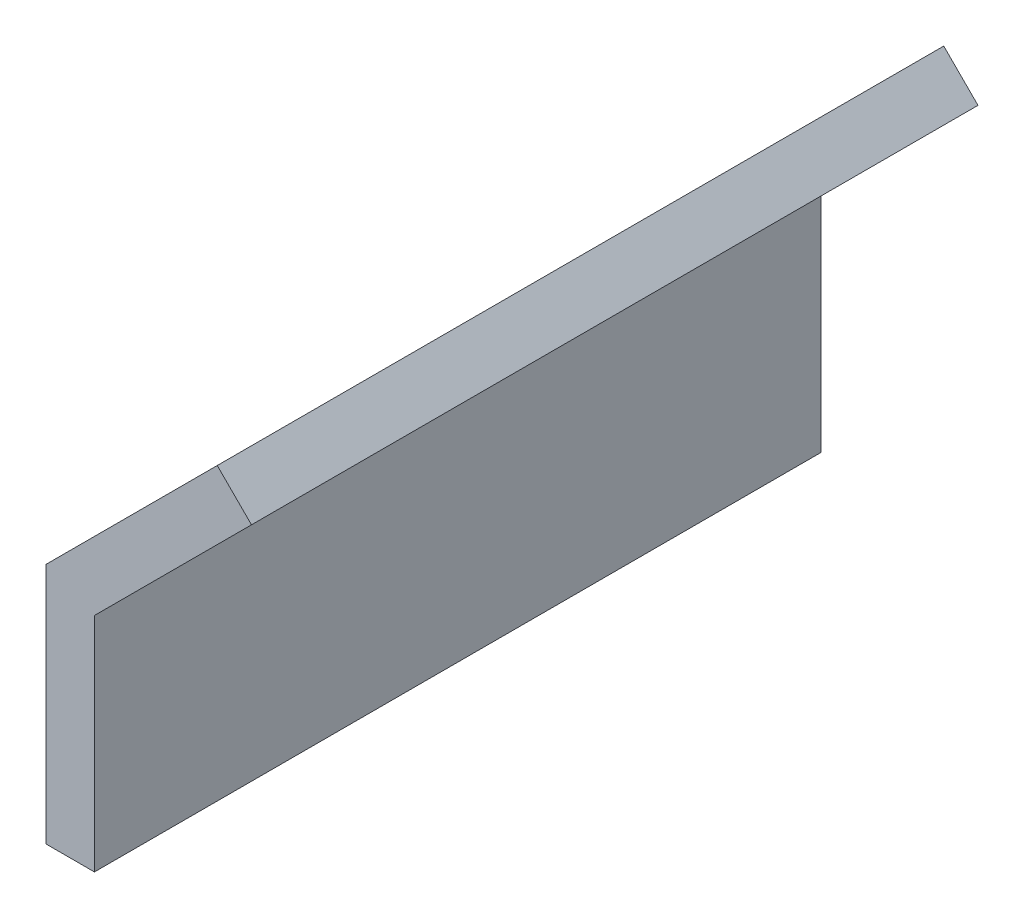
SolidWorks part; units mm, degrees
ref_plane "Front Plane" through (0, 0, 0) normal (0, 0, 1) x (1, 0, 0)
ref_plane "Top Plane" through (0, 0, 0) normal (0, 1, 0) x (1, 0, 0)
ref_plane "Right Plane" through (0, 0, 0) normal (1, 0, 0) x (0, 0, -1)
sketch "Sketch1" plane through (0, 0, 0) normal (0, 0, 1) x (1, 0, 0)
  line L0 (0, 0) -> (2.54, 0)
  line L1 (2.54, 0) -> (2.54, 11.6479)
  line L2 (2.54, 11.6479) -> (10.7763, 19.8842)
  line L3 (10.7763, 19.8842) -> (8.9803, 21.6803)
  line L4 (8.9803, 21.6803) -> (0, 12.7)
  line L5 (0, 12.7) -> (0, 0)
  line L6 (0, 12.7) -> (2.54, 11.6479) construction
  point P3 (15.5928, 42.2741)
  point P8 (2.54, 25.0721)
  dimension "D1" = 135
  dimension "D2" = 12.7
  dimension "D3" = 2.54
  dimension "D4" = 12.7
extrude "Boss-Extrude1" add sketch "Sketch1" along normal blind 38.1
